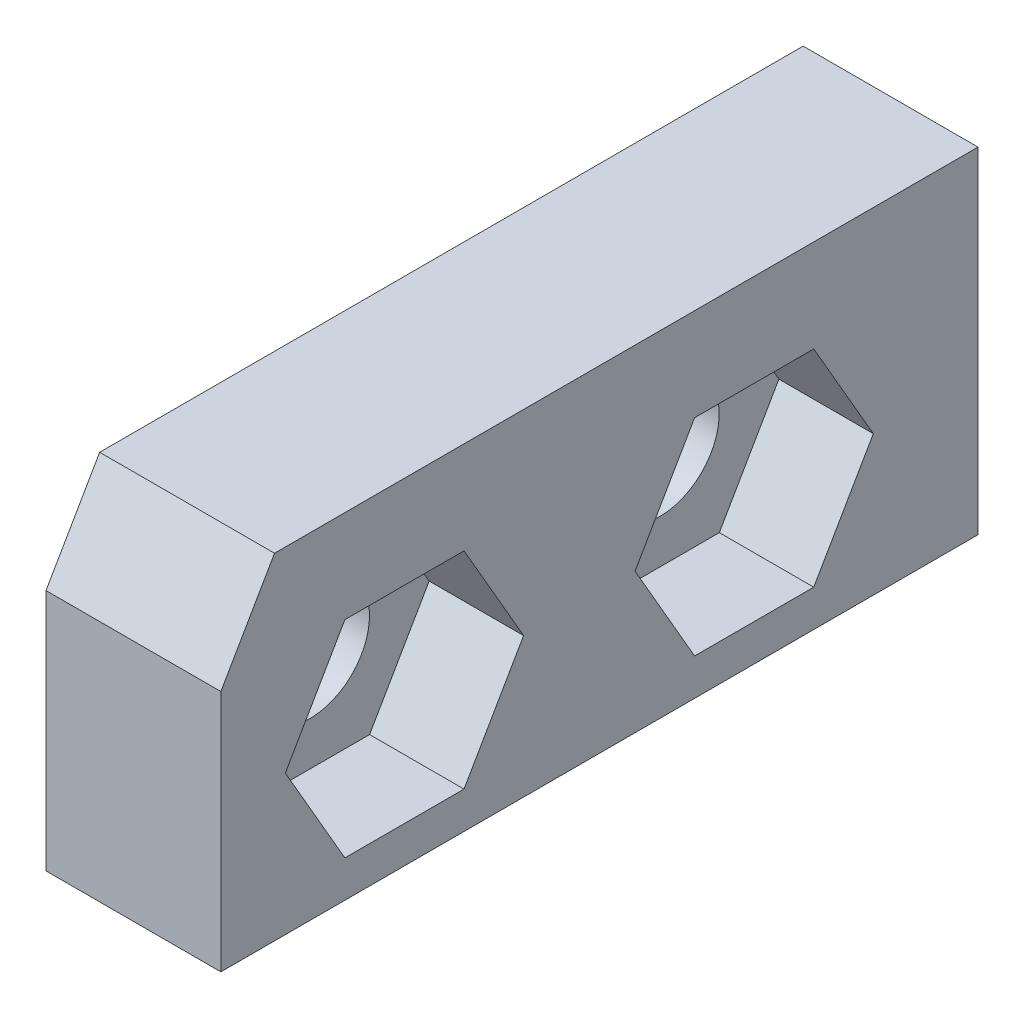
SolidWorks part; units mm, degrees
ref_plane "Front Plane" through (0, 0, 0) normal (0, 0, 1) x (1, 0, 0)
ref_plane "Top Plane" through (0, 0, 0) normal (0, 1, 0) x (1, 0, 0)
ref_plane "Right Plane" through (0, 0, 0) normal (1, 0, 0) x (0, 0, -1)
sketch "Sketch1" plane through (0, 0, 0) normal (1, 0, 0) x (0, 0, -1)
  line L0 (50, 112.9) -> (50, 122.5)
  line L1 (50, 122.5) -> (28.35, 122.5)
  line L2 (28.35, 122.5) -> (28.35, 112.9)
  line L3 (28.35, 112.9) -> (50, 112.9)
extrude "Keeper" add sketch "Sketch1" along normal blind 5 from offset 0.55
sketch "Sketch2" plane through (0, 0, 0) normal (1, 0, 0) x (0, 0, -1)
  line L0 (21.8, 108.5) -> (21.8, 122.7)
  line L1 (21.8, 122.7) -> (30, 122.7)
  line L2 (30, 122.7) -> (21.8, 108.5)
extrude "Bulkhead chamfer" cut sketch "Sketch2" along normal blind 5.4 from offset 0.35
sketch "Sketch3" plane through (0, 0, 0) normal (1, 0, 0) x (0, 0, -1)
  circle A0 centre (33.6, 116.9) radius 1.7
  circle A1 centre (43.6, 116.9) radius 1.7
extrude "Tab bolt holes" cut sketch "Sketch3" along normal blind 5.4 from offset 0.35
sketch "Sketch4" plane through (0, 0, 0) normal (1, 0, 0) x (0, 0, -1)
  line L0 (31.8968, 119.85) -> (30.1936, 116.9)
  line L1 (30.1936, 116.9) -> (31.8968, 113.95)
  line L2 (31.8968, 113.95) -> (35.3032, 113.95)
  line L3 (35.3032, 113.95) -> (37.0064, 116.9)
  line L4 (37.0064, 116.9) -> (35.3032, 119.85)
  line L5 (35.3032, 119.85) -> (31.8968, 119.85)
  line L6 (41.8968, 119.85) -> (40.1936, 116.9)
  line L7 (40.1936, 116.9) -> (41.8968, 113.95)
  line L8 (41.8968, 113.95) -> (45.3032, 113.95)
  line L9 (45.3032, 113.95) -> (47.0064, 116.9)
  line L10 (47.0064, 116.9) -> (45.3032, 119.85)
  line L11 (45.3032, 119.85) -> (41.8968, 119.85)
extrude "Tab nut pockets" cut sketch "Sketch4" along normal blind 2.9 from offset 2.85
